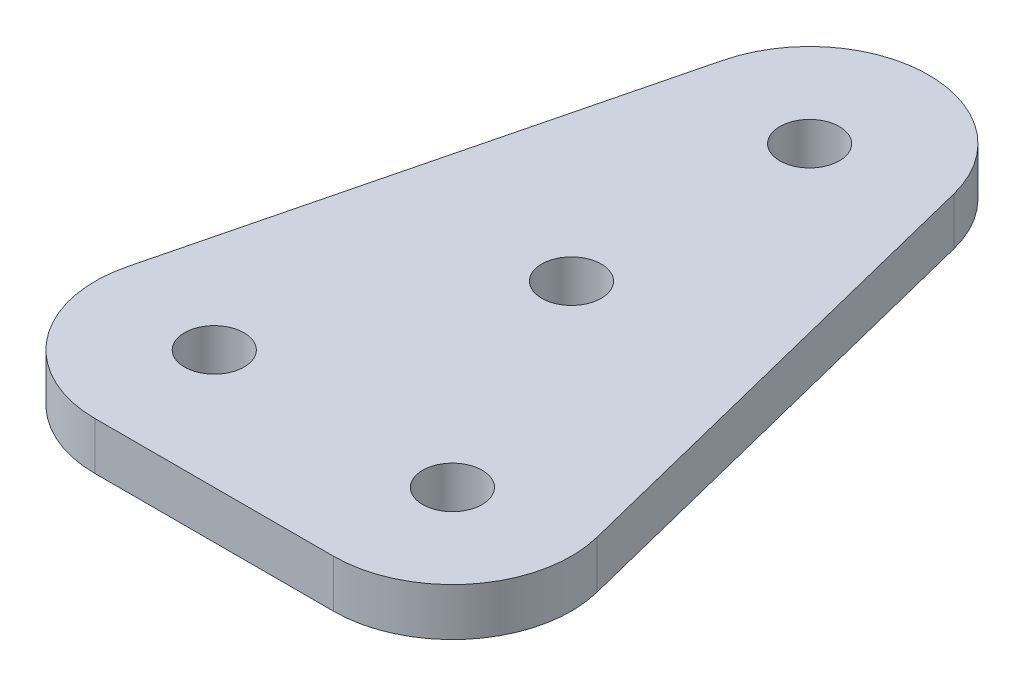
SolidWorks part; units mm, degrees
material "Thornel Mat VMA"
ref_plane "Front Plane" through (0, 0, 0) normal (0, 0, 1) x (1, 0, 0)
ref_plane "Top Plane" through (0, 0, 0) normal (0, 1, 0) x (1, 0, 0)
ref_plane "Right Plane" through (0, 0, 0) normal (1, 0, 0) x (0, 0, -1)
sketch "Sketch1" plane through (0, 0, 0) normal (0, 1, 0) x (1, 0, 0)
  line L0 (0, 48.5704) -> (0, -31.4177) construction
  line L1 (-41.6317, 0) -> (40.9422, 0) construction
  line L2 (-9.7014, 42.4254) -> (-19.7014, 2.4254)
  line L3 (-10, -10) -> (10, -10)
  line L4 (9.7014, 42.4254) -> (19.7014, 2.4254)
  circle A0 centre (10, 0) radius 2.5
  circle A1 centre (-10, 0) radius 2.5
  circle A2 centre (0, 20) radius 2.5
  circle A3 centre (0, 40) radius 2.5
  arc A4 (9.7014, 42.4254) -> (-9.7014, 42.4254) centre (0, 40) ccw
  arc A5 (-19.7014, 2.4254) -> (-10, -10) centre (-10, 0) ccw
  arc A6 (10, -10) -> (19.7014, 2.4254) centre (10, 0) ccw
  dimension "D1" = 5
  dimension "D3" = 5
  dimension "D5" = 5
  dimension "D7" = 20
  dimension "D8" = 20
  dimension "D9" = 20
  dimension "D2" = 10
  dimension "D4" = 20
  dimension "D6" = 40
extrude "Boss-Extrude1" add sketch "Sketch1" along normal blind 4
